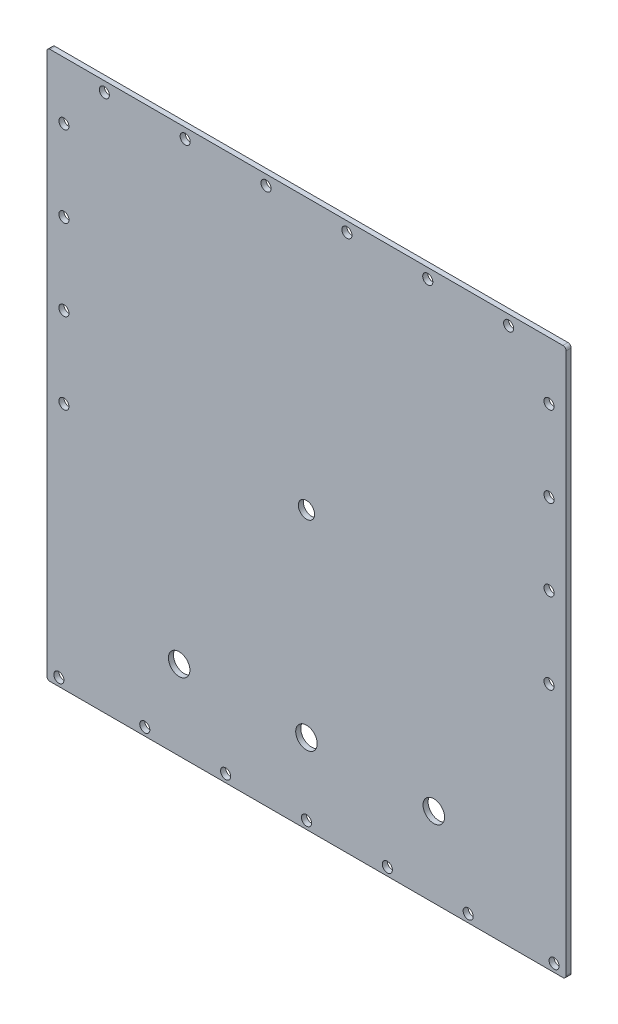
SolidWorks part; units mm, degrees
material "6061 Alloy"
ref_plane "Front Plane" through (0, 0, 0) normal (0, 0, 1) x (1, 0, 0)
ref_plane "Top Plane" through (0, 0, 0) normal (0, 1, 0) x (1, 0, 0)
ref_plane "Right Plane" through (0, 0, 0) normal (1, 0, 0) x (0, 0, -1)
sketch "Sketch2" plane through (0, 0, 0) normal (0, 0, 1) x (1, 0, 0)
  line L0 (0, -176.7623) -> (165.1, -176.7623)
  line L1 (0, 0) -> (165.1, 0)
  line L5 (82.55, 0) -> (82.55, -176.7623) construction
  line L6 (165.1, 0) -> (165.1, -176.7623)
  line L7 (0, 0) -> (0, -176.7623)
  line L8 (0, 0) -> (0, -176.7623)
  line L9 (0, -171.98) -> (165.1, -171.98)
  line L10 (1, 0) -> (1, -171.98)
  line L11 (164.1, -171.98) -> (164.1, 0)
  circle A31 centre (31.75, -169.48) radius 1.5875
  circle A32 centre (57.15, -169.48) radius 1.5875
  circle A33 centre (82.55, -169.48) radius 1.5875
  circle A34 centre (107.95, -169.48) radius 1.5875
  circle A35 centre (133.35, -169.48) radius 1.5875
  circle A63 centre (6.35, -18.05) radius 1.5875
  circle A65 centre (160.3375, -169.48) radius 1.5875
  circle A66 centre (4.7625, -169.48) radius 1.5875
  circle A67 centre (82.55, -85) radius 2.5527
  circle A69 centre (19.05, -3.175) radius 1.5875
  circle A70 centre (44.45, -3.175) radius 1.5875
  circle A71 centre (69.85, -3.175) radius 1.5875
  circle A72 centre (95.25, -3.175) radius 1.5875
  circle A73 centre (120.65, -3.175) radius 1.5875
  circle A74 centre (146.05, -3.175) radius 1.5875
  circle A76 centre (6.35, -43.45) radius 1.5875
  circle A77 centre (6.35, -68.85) radius 1.5875
  circle A78 centre (6.35, -94.25) radius 1.5875
  circle A81 centre (158.75, -68.85) radius 1.5875
  circle A82 centre (158.75, -94.25) radius 1.5875
  circle A83 centre (158.75, -43.45) radius 1.5875
  circle A84 centre (158.75, -18.05) radius 1.5875
  dimension "D9" = 3.175
  dimension "D4" = 3.175
  dimension "D21" = 5.1054
  dimension "D1" = 165.1
  dimension "D23" = 25.4
  dimension "D5" = 176.7623
  dimension "D8" = 31.75
  dimension "D11" = 7.2823
  dimension "D10" = 19.05
  dimension "D12" = 3.175
  dimension "D14" = 25.4
  dimension "D3" = 18.05
  dimension "D6" = 6.35
  dimension "D15" = 25.4
  dimension "D16" = 2.5
  dimension "D17" = 4.7625
  dimension "D18" = 1
  dimension "D19" = 1
  dimension "D20" = 85
  dimension "D22" = 5
  dimension "D13" = 3
  dimension "D7" = 4
extrude "Boss-Extrude2" add sketch "Sketch2" along normal blind 1.5875
fillet "Fillet1" radius 1 4 edges at (1, -171.98, 0.7937) (1, 0, 0.7937) (164.1, 0, 0.7937) (164.1, -171.98, 0.7937)
sketch "Sketch3" plane through (0, 0, 1.5875) normal (0, 0, 1) x (1, 0, 0)
  line L0 (2, -171.98) -> (163.1, -171.98) construction
  line L2 (1, -1) -> (1, -170.98) construction
  circle A0 centre (42.55, -146.9721) radius 3.38
  circle A1 centre (82.55, -146.9721) radius 3.38
  circle A2 centre (122.55, -146.9721) radius 3.38
  point P8 (0, 0)
  dimension "D4" = 6.76
  dimension "D1" = 40
  dimension "D2" = 40
  dimension "D3" = 25.0079
  dimension "D5" = 41.55
extrude "Cut-Extrude1" cut sketch "Sketch3" against normal through all both and the other way through all
equation "\"D19@Sketch2\"=\"D18@Sketch2\""
equation "\"D9@Sketch2\"=\"D4@Sketch2\""
